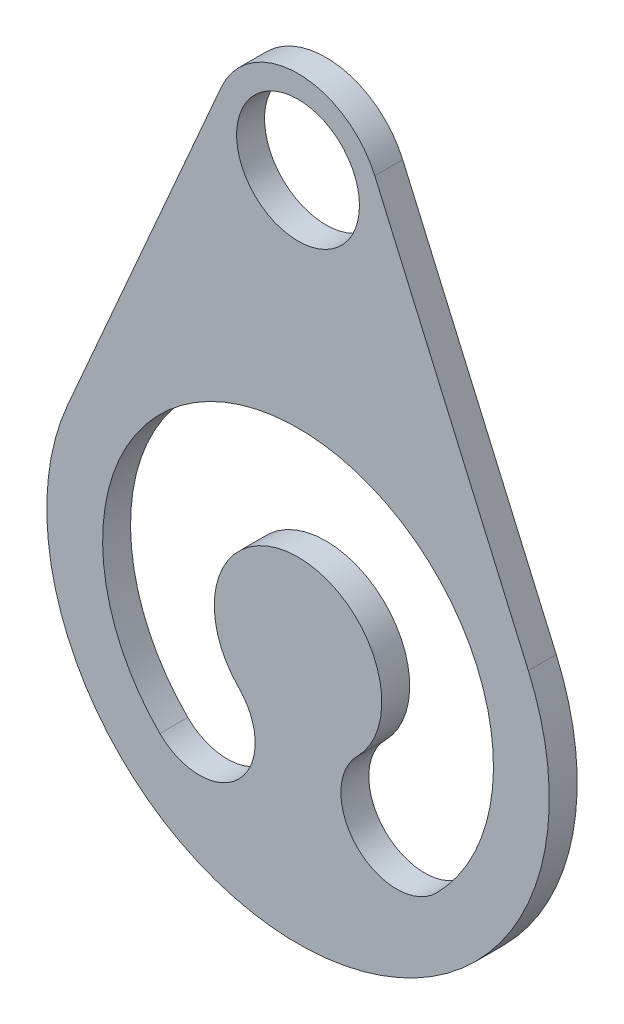
SolidWorks part; units mm, degrees
ref_plane "Alzado" through (0, 0, 0) normal (0, 0, 1) x (1, 0, 0)
ref_plane "Planta" through (0, 0, 0) normal (0, 1, 0) x (1, 0, 0)
ref_plane "Vista lateral" through (0, 0, 0) normal (1, 0, 0) x (0, 0, -1)
sketch "Croquis1" plane through (0, 0, 0) normal (0, 0, 1) x (1, 0, 0)
  line L0 (-17.6777, -17.6777) -> (0, 0) construction
  line L1 (0, 0) -> (17.6777, -17.6777) construction
  line L2 (0, -45) -> (0, 90) construction
  line L3 (-13.7477, 81) -> (-41.2432, 18)
  line L4 (13.7477, 81) -> (41.2432, 18)
  arc A0 (-41.2432, 18) -> (41.2432, 18) centre (0, 0) ccw
  arc A1 (17.6777, -17.6777) -> (-17.6777, -17.6777) centre (0, 0) ccw construction
  arc A2 (24.7487, -24.7487) -> (-24.7487, -24.7487) centre (0, 0) ccw
  arc A3 (10.6066, -10.6066) -> (-10.6066, -10.6066) centre (0, 0) ccw
  arc A4 (10.6066, -10.6066) -> (24.7487, -24.7487) centre (17.6777, -17.6777) ccw
  arc A5 (-24.7487, -24.7487) -> (-10.6066, -10.6066) centre (-17.6777, -17.6777) ccw
  circle A6 centre (0, 75) radius 11
  arc A7 (13.7477, 81) -> (-13.7477, 81) centre (0, 75) ccw
  point P3 (0, 25)
  dimension "D1" = 90
  dimension "D2" = 25
  dimension "D3" = 10
  dimension "D5" = 22
  dimension "D6" = 30
  dimension "D4" = 90
  dimension "D7" = 75
extrude "Saliente-Extruir1" add sketch "Croquis1" along normal blind 5
